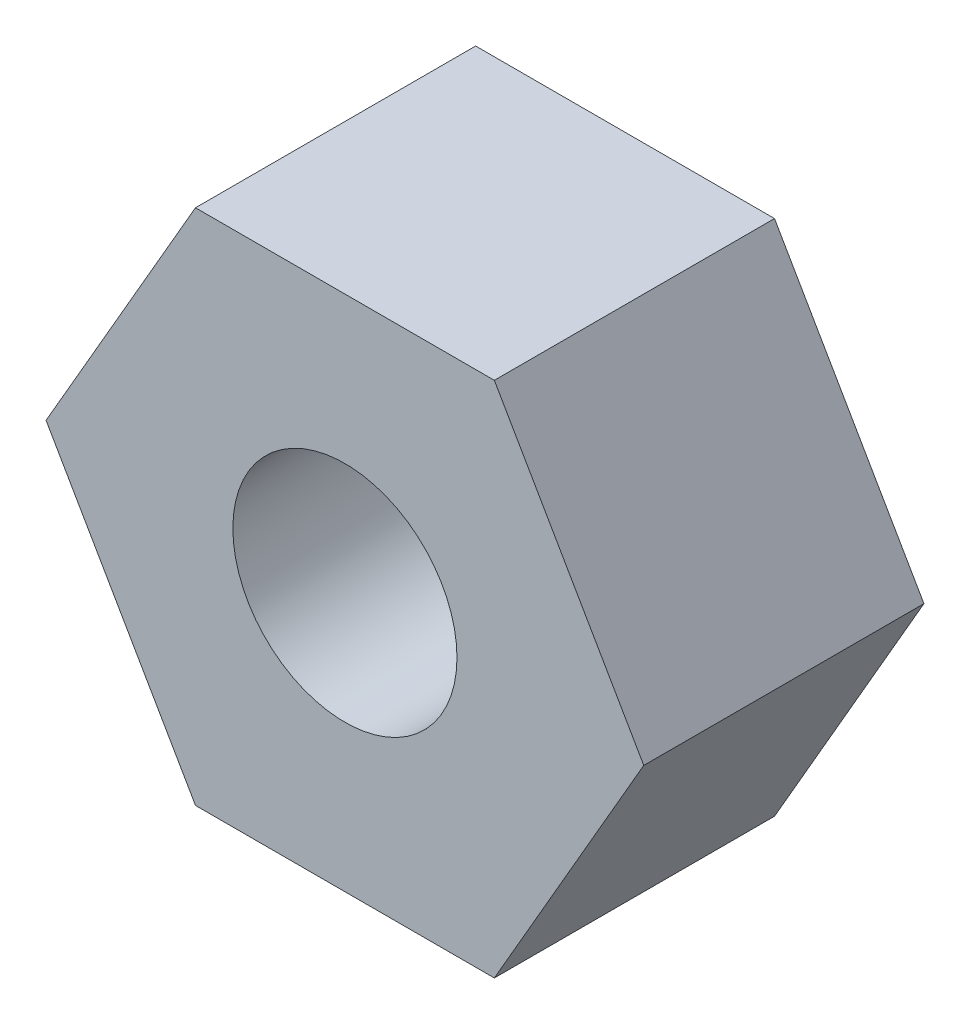
SolidWorks part; units mm, degrees
ref_plane "前视基准面" through (0, 0, 0) normal (0, 0, 1) x (1, 0, 0)
ref_plane "上视基准面" through (0, 0, 0) normal (0, 1, 0) x (1, 0, 0)
ref_plane "右视基准面" through (0, 0, 0) normal (1, 0, 0) x (0, 0, -1)
sketch "草图1" plane through (0, 0, 0) normal (0, 0, 1) x (1, 0, 0)
  line L1 (1.6, 2.7713) -> (-1.6, 2.7713)
  line L2 (-1.6, 2.7713) -> (-3.2, 0)
  line L3 (-3.2, 0) -> (-1.6, -2.7713)
  line L4 (-1.6, -2.7713) -> (1.6, -2.7713)
  line L5 (1.6, -2.7713) -> (3.2, 0)
  line L6 (3.2, 0) -> (1.6, 2.7713)
  circle A0 centre (0, 0) radius 2.7713 construction
  circle A1 centre (0, 0) radius 1.5
  dimension "D2" = 3
  dimension "D1" = 3.2
extrude "凸台-拉伸1" add sketch "草图1" along normal blind 3 contours L1 L2 L3 L4 L5 L6
sketch "草图2" plane through (0, 0, 0) normal (0, 0, -1) x (-1, 0, 0)
  circle A0 centre (0, 0) radius 1.2
  dimension "D1" = 2.4
extrude "切除-拉伸1" cut sketch "草图2" against normal blind 3
